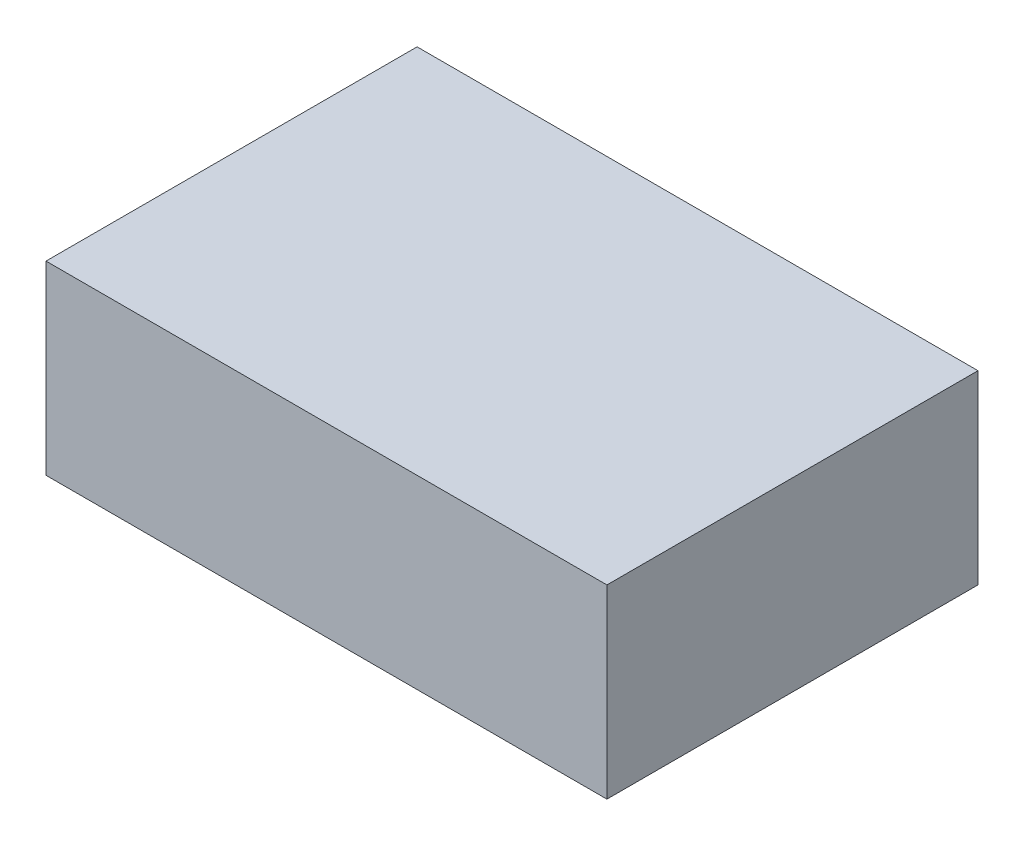
SolidWorks part; units mm, degrees
ref_plane "Front Plane" through (0, 0, 0) normal (0, 0, 1) x (1, 0, 0)
ref_plane "Top Plane" through (0, 0, 0) normal (0, 1, 0) x (1, 0, 0)
ref_plane "Right Plane" through (0, 0, 0) normal (1, 0, 0) x (0, 0, -1)
sketch "Sketch1" plane through (0, 0, 0) normal (0, 0, 1) x (1, 0, 0)
  line L1 (-65, -21.5) -> (65, -21.5)
  line L2 (-65, -21.5) -> (-65, 21.5)
  line L3 (-65, 21.5) -> (65, 21.5)
  line L4 (65, -21.5) -> (65, 21.5)
  line L5 (-65, -21.5) -> (65, 21.5) construction
  line L6 (-65, 21.5) -> (65, -21.5) construction
  point P0 (0, 0)
  dimension "D1" = 130
  dimension "D2" = 43
extrude "Boss-Extrude1" add sketch "Sketch1" along normal mid plane 86
hole_wizard "M3x0.5 Tapped Hole1" positions "Sketch2" profile "Sketch3" tap size "M3x0.5" standard "ANSI Metric"
sketch "Sketch2" plane through (0, -21.5, 0) normal (0, -1, 0) x (-1, 0, 0)
  line L0 (65, -43) -> (-65, -43) construction
  line L1 (65, -43) -> (65, 43) construction
  line L2 (-65, -43) -> (-65, 43) construction
  point P0 (60, -24.7)
  point P2 (-60, -24.7)
  point P4 (-60, 25.3)
  point P6 (60, 25.3)
  dimension "D1" = 18.3
  dimension "D2" = 50
  dimension "D3" = 5
  dimension "D4" = 5
sketch "Sketch3" plane through (-60, -21.5, 24.7) normal (1, 0, 0) x (0, 0, -1)
  line L0 (0, 0) -> (0, 2.7511)
  line L1 (0, 2.7511) -> (1.25, 2)
  line L2 (1.25, 2) -> (1.25, 0)
  line L5 (1.25, 0) -> (0, 0)
  line L10 (0, 2.7511) -> (-1.25, 2) construction
  line L11 (0, -6.35) -> (0, 107.95) construction
  dimension "Tap Drill Dia." = 2.5
  dimension "Tap Drill Depth" = 2
  dimension "Drill Angle" = 118
cosmetic thread "Hole Thread1" parameters "D1"=2, "D2"=3
cosmetic thread "Hole Thread2" parameters "D1"=2, "D2"=3
cosmetic thread "Hole Thread3" parameters "D1"=2, "D2"=3
cosmetic thread "Hole Thread4" parameters "D1"=2, "D2"=3
sketch "Sketch4" plane through (0, 0, -43) normal (0, 0, -1) x (-1, 0, 0)
  circle A0 centre (0, 0) radius 12.7
  dimension "D1" = 25.4
extrude "Cut-Extrude1" cut sketch "Sketch4" against normal blind 2.54
equation "\"D1@Sketch1\"=130mm"
equation "\"D2@Sketch1\"=43mm"
equation "\"D1@Boss-Extrude1\"=86mm"
equation "\"D1@Sketch2\"=18.3mm"
equation "\"D2@Sketch2\"=50mm"
equation "\"D3@Sketch2\"=5mm"
equation "\"D4@Sketch2\"=\"D3@Sketch2\""
